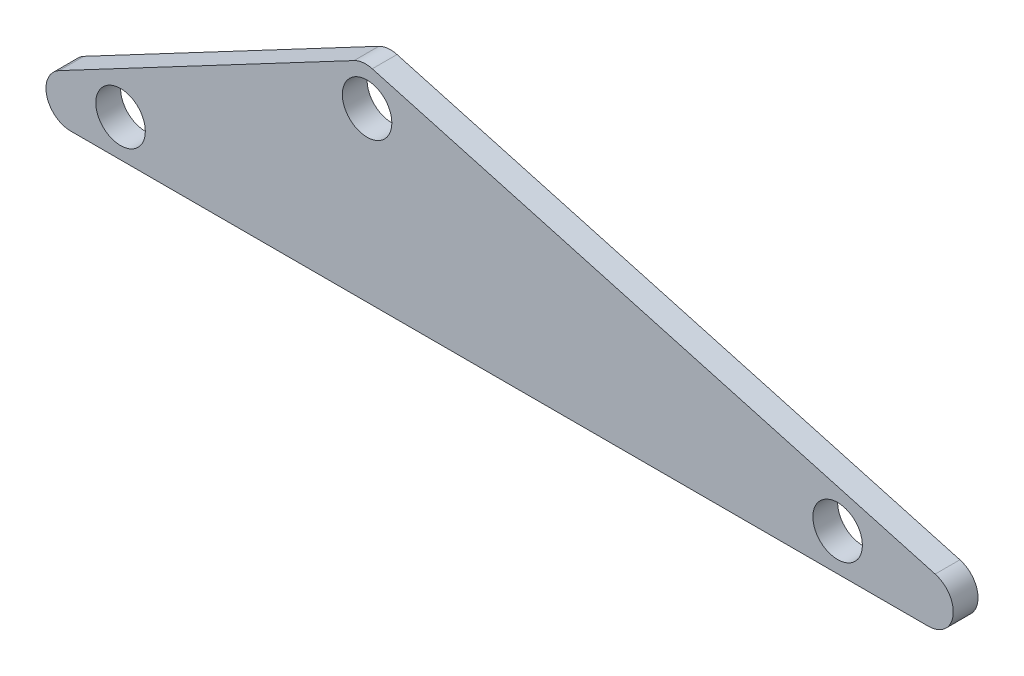
SolidWorks part; units mm, degrees
ref_plane "Front Plane" through (0, 0, 0) normal (0, 0, 1) x (1, 0, 0)
ref_plane "Top Plane" through (0, 0, 0) normal (0, 1, 0) x (1, 0, 0)
ref_plane "Right Plane" through (0, 0, 0) normal (1, 0, 0) x (0, 0, -1)
sketch "Sketch1" plane through (0, 0, 0) normal (0, 0, 1) x (1, 0, 0)
  line L3 (6.0853, 5.4691) -> (-5.8304, -0.8397)
  line L4 (-5.3625, -2.7234) -> (29.2976, -2.7234)
  line L5 (29.5649, -0.7598) -> (6.8205, 5.549)
  circle A0 centre (6.6113, 4.0504) radius 1
  circle A1 centre (-3.3496, -1.2234) radius 1
  circle A2 centre (25.6243, -1.2234) radius 1
  arc A3 (29.2976, -2.7234) -> (29.5649, -0.7598) centre (29.2976, -1.7234) ccw
  arc A4 (-5.8304, -0.8397) -> (-5.3625, -2.7234) centre (-5.3625, -1.7234) ccw
  arc A5 (6.0853, 5.4691) -> (6.8205, 5.549) centre (6.5532, 4.5854) cw
  dimension "D1" = 2
  dimension "D4" = 1
  dimension "D2" = 28.9739
  dimension "D3" = 9.9609
extrude "Boss-Extrude1" add sketch "Sketch1" along normal mid plane 1 contours A0 | A2 | L3 A4 L4 A3 L5 A5 | A1
